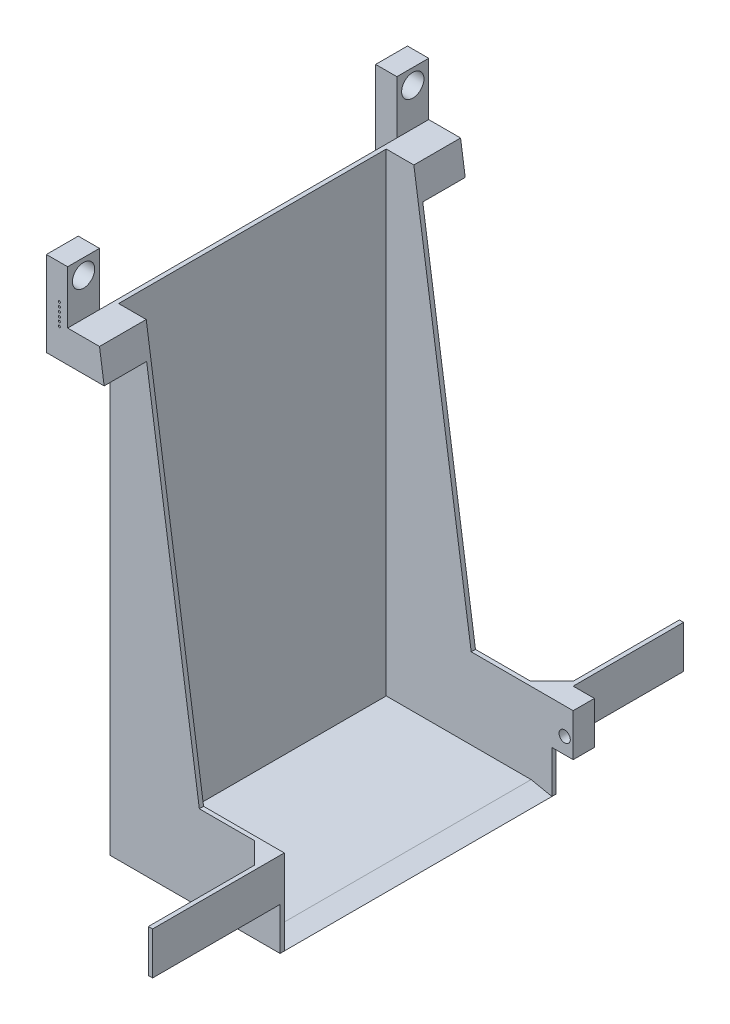
SolidWorks part; units mm, degrees
material "Custom Plastic"
ref_plane "Front Plane" through (0, 0, 0) normal (0, 0, 1) x (1, 0, 0)
ref_plane "Top Plane" through (0, 0, 0) normal (0, 1, 0) x (1, 0, 0)
ref_plane "Right Plane" through (0, 0, 0) normal (1, 0, 0) x (0, 0, -1)
sketch "Sketch2" plane through (0, 0, 0) normal (0, 0, 1) x (1, 0, 0)
  line L4 (15, 225) -> (0, 225)
  line L6 (0, 0) -> (0, 225)
  line L14 (80, 40) -> (42, 40)
  line L15 (42, 40) -> (15, 225)
  line L16 (80, 40) -> (80, 0)
  line L19 (0, 0) -> (80, 0)
  point P0 (69, 44.3962)
  dimension "D2" = 15
  dimension "D5" = 42
  dimension "D1" = 225
  dimension "D3" = 40
  dimension "D4" = 80
extrude "Boss-Extrude2" add sketch "Sketch2" along normal mid plane 130
sketch "Sketch5" plane through (0, 0, 0) normal (0, 0, 1) x (1, 0, 0)
  line L1 (2, 2) -> (70.202, 2)
  line L4 (70.202, 2) -> (80, 0)
  line L6 (0, 225) -> (0, 0) construction
  line L13 (80, 0) -> (80, 40) construction
  line L16 (15, 225) -> (42, 40)
  line L17 (80, 0) -> (80, 40)
  line L18 (15, 225) -> (2, 225)
  line L19 (15, 225) -> (0, 225) construction
  line L20 (2, 225) -> (2, 2)
  line L21 (0, 0) -> (80, 0) construction
  line L22 (80, 40) -> (42, 40)
  dimension "D2" = 2
  dimension "D3" = 10
  dimension "D1" = 2
extrude "Cut-Extrude1" cut sketch "Sketch5" against normal mid plane 126
sketch "Sketch25" plane through (0, 0, 65) normal (0, 0, 1) x (1, 0, 0)
  line L0 (17.1892, 210) -> (15, 225)
  line L1 (0, 225) -> (15, 225)
  line L2 (0, 225) -> (0, 210)
  line L3 (0, 210) -> (17.1892, 210)
  line L5 (42, 40) -> (15, 225) construction
  line L6 (15, 225) -> (0, 225) construction
extrude "Boss-Extrude6" add sketch "Sketch25" along normal blind 20
sketch "Sketch26" plane through (0, 0, 0) normal (-1, 0, 0) x (0, 0, 1)
  line L1 (85, 210) -> (70, 210)
  line L2 (85, 210) -> (85, 250)
  line L3 (85, 250) -> (70, 250)
  line L4 (70, 210) -> (70, 250)
  dimension "D1" = 15
  dimension "D2" = 40
extrude "Boss-Extrude7" add sketch "Sketch26" along normal blind 10
sketch "Sketch27" plane through (0, 0, 85) normal (0, 0, 1) x (1, 0, 0)
  line L0 (16.0946, 217.5) -> (-10, 217.5) construction
  line L1 (17.1892, 210) -> (15, 225) construction
  line L2 (-10, 210) -> (-10, 250) construction
  line L7 (-3.9054, 233.7) -> (-3.9054, 231.7) construction
  line L8 (-3.9054, 231.7) -> (-3.9054, 229.7) construction
  line L9 (-3.9054, 229.7) -> (-3.9054, 227.7) construction
  line L10 (-3.9054, 227.7) -> (-3.9054, 225.7) construction
  line L11 (-3.9054, 225.7) -> (-3.9054, 223.7) construction
  line L12 (-3.9054, 223.7) -> (-3.9054, 217.5) construction
  circle A0 centre (-3.9054, 217.5) radius 5 construction
  circle A1 centre (-3.9054, 231.7) radius 0.5
  circle A2 centre (-3.9054, 233.7) radius 0.5
  circle A3 centre (-3.9054, 229.7) radius 0.5
  circle A4 centre (-3.9054, 227.7) radius 0.5
  circle A5 centre (-3.9054, 225.7) radius 0.5
  circle A6 centre (-3.9054, 223.7) radius 0.5
  point P9 (-26.272, 217.5)
  point P25 (39.3767, 235.9925)
  point P26 (0, 0)
  point P27 (-32.3903, 217.5)
  dimension "D1" = 10
  dimension "D4" = 1
  dimension "D2" = 20
  dimension "D5" = 6.2
  dimension "D6" = 2
extrude "Cut-Extrude3" cut sketch "Sketch27" against normal blind 5
sketch "Sketch29" plane through (0, 0, 0) normal (1, 0, 0) x (0, 0, -1)
  line L0 (-77.5, 242.75) -> (-77.5, 250) construction
  line L1 (-85, 250) -> (-70, 250) construction
  circle A0 centre (-77.5, 242.75) radius 5.25
  point P2 (-77.5, 243.1889)
  dimension "D1" = 10.5
  dimension "D2" = 7.25
extrude "Cut-Extrude4" cut sketch "Sketch29" against normal up to surface (10 mm away) up to face at (-10, 230, 77.5)
ref_plane "Plane1" through (0, 0, 0) normal (0, 0, -1) x (-1, 0, 0)
sketch "Sketch30" plane through (0, 0, 65) normal (0, 0, 1) x (1, 0, 0)
  line L1 (80, 40) -> (78, 40)
  line L2 (80, 40) -> (80, 20)
  line L3 (80, 20) -> (78, 20)
  line L4 (78, 40) -> (78, 20)
  dimension "D1" = 20
  dimension "D2" = 2
extrude "Boss-Extrude8" add sketch "Sketch30" along normal blind 60
chamfer "Chamfer1" distance 10 angle 45 1 edges at (78, 30, 65)
mirror "Mirror3" about plane through (0, 0, 0) normal (0, 0, -1) of bodies 141
sketch "Sketch32" plane through (80, 0, 0) normal (1, 0, 0) x (0, 0, -1)
  line L0 (125, 20) -> (65, 20) construction
  line L1 (63, 40) -> (73, 40)
  line L2 (63, 40) -> (63, 20)
  line L3 (63, 20) -> (73, 20)
  line L4 (73, 40) -> (73, 20)
  dimension "D1" = 10
extrude "Boss-Extrude9" add sketch "Sketch32" along normal blind 10
sketch "Sketch33" plane through (0, 0, -63) normal (0, 0, 1) x (1, 0, 0)
  line L0 (80, 20) -> (80, 40) construction
  line L2 (80, 20) -> (80, 40) construction
  line L3 (86, 27.5) -> (86, 30) construction
  line L4 (80, 30) -> (86, 30) construction
  line L5 (0, 0) -> (80, 0) construction
  line L6 (0, 0) -> (80, 0) construction
  line L7 (80, 0) -> (80, 27.5) construction
  line L8 (80, 27.5) -> (86, 27.5) construction
  circle A6 centre (86, 27.5) radius 2.65
  dimension "D1" = 6
  dimension "D2" = 27.5
  dimension "D3" = 5.3
extrude "Cut-Extrude5" cut sketch "Sketch33" against normal up to surface (10 mm away) up to face at (85, 30, -73)
equation "\"ScooperHeight\"= 24.5cm"
equation "\"ScooperTopLength\"=1.5"
equation "\"D2@Sketch2\"=\"ScooperTopLength\""
equation "\"ScooperWallThickness\"=0.2"
equation "\"D2@Sketch5\"=\"ScooperWallThickness\""
equation "\"ScooperEdgeLength\"=1"
equation "\"D3@Sketch5\"=\"ScooperEdgeLength\""
equation "\"ScooperInnerWidth\"=15.5"
equation "\"ScooperOuterWidth\"= 13cm"
equation "\"D1@Cut-Extrude1\"=\"ScooperOuterWidth\"-2*\"ScooperWallThickness\""
equation "\"D1@Boss-Extrude2\"=\"ScooperOuterWidth\""
equation "\"CounterWeightHolderHeight\"=1"
equation "\"CounterWeightHolderLength\"= 3cm"
equation "\"CounterWeightWidth\"= 1.5cm"
equation "\"y_HoleOffset\"=1.8"
equation "\"ScooperHandleWidth\"= 2.5cm"
equation "\"HandleHoleDiameter\"=1"
equation "\"ScooperAxisHoleDiameter\"=0.5"
equation "\"EraserCutOutHeight\"=2"
equation "\"BoltHoleDiameter\"=1.05"
equation "\"D1@Sketch29\"=\"BoltHoleDiameter\""
equation "\"D2@Sketch29\"=\"BoltHoleDiameter\"/2+2mm"
equation "\"ScooperFloorLength\"=8"
equation "\"D4@Sketch2\"=\"ScooperFloorLength\""
